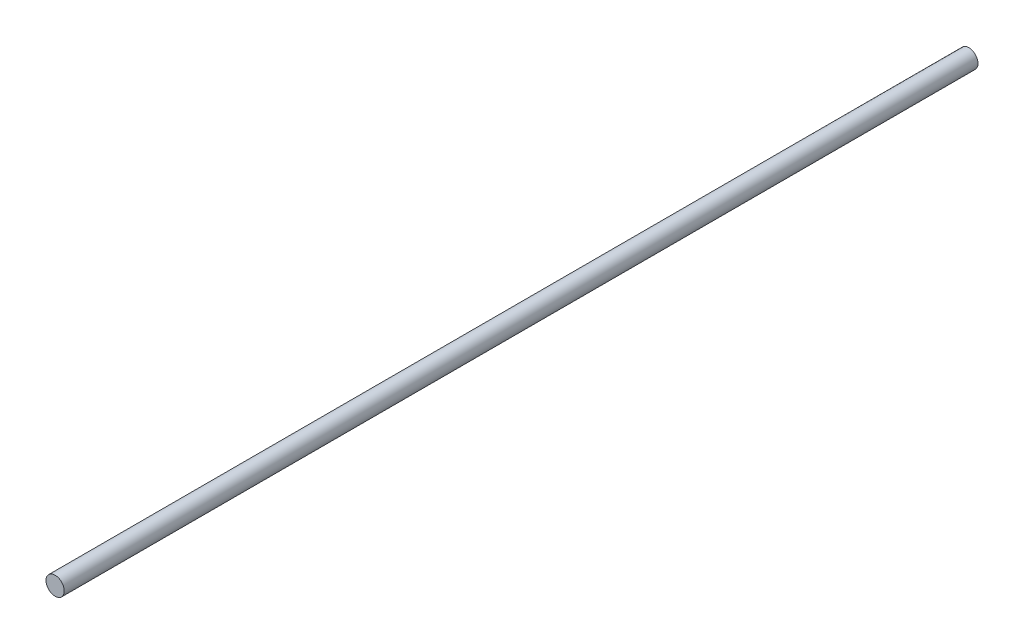
SolidWorks part; units mm, degrees
ref_plane "Front Plane" through (0, 0, 0) normal (0, 0, 1) x (1, 0, 0)
ref_plane "Top Plane" through (0, 0, 0) normal (0, 1, 0) x (1, 0, 0)
ref_plane "Right Plane" through (0, 0, 0) normal (1, 0, 0) x (0, 0, -1)
sketch "Sketch2" plane through (0, 0, 0) normal (0, 0, 1) x (1, 0, 0)
  circle A0 centre (0, 0) radius 10
  dimension "D1" = 20
extrude "Boss-Extrude1" add sketch "Sketch2" along normal blind 1000
